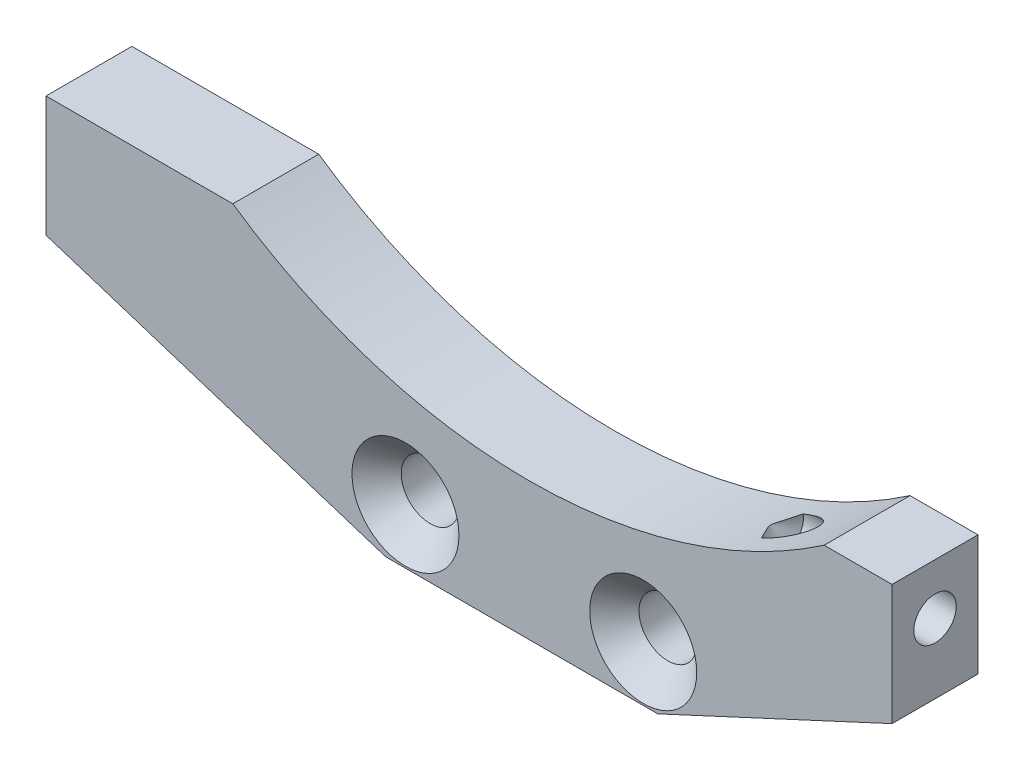
SolidWorks part; units mm, degrees
ref_plane "Piano frontale" through (0, 0, 0) normal (0, 0, 1) x (1, 0, 0)
ref_plane "Piano superiore" through (0, 0, 0) normal (0, 1, 0) x (1, 0, 0)
ref_plane "Piano destro" through (0, 0, 0) normal (1, 0, 0) x (0, 0, -1)
sketch "Schizzo4" plane through (0, 0, 0) normal (0, 0, 1) x (1, 0, 0)
  line L0 (0, 0) -> (16.02, 0)
  line L1 (16.02, 0) -> (29.82, 6.4)
  line L2 (29.82, 6.4) -> (29.82, 13.5)
  line L3 (29.82, 13.5) -> (-20, 13.5)
  line L4 (-20, 13.5) -> (-20, 6.4)
  line L5 (-20, 6.4) -> (0, 0)
  arc A0 (-9, 13.5) -> (25.82, 13.5) centre (8.41, 38.8656) ccw
  point P10 (8.41, 8.1)
  dimension "D8" = 5.4
  dimension "D1" = 49.82
  dimension "D2" = 7.1
  dimension "D3" = 13.8
  dimension "D4" = 13.5
  dimension "D5" = 20
  dimension "D6" = 11
  dimension "D7" = 4
extrude "Estrusione-Estrusione1" add sketch "Schizzo4" along normal blind 5.06 contours A0 L3 L4 L5 L0 L1 L2
ref_plane "Piano1" through (4.91, 0, 0) normal (-1, 0, 0) x (0, 0, 1)
hole_wizard "Foro filettato M3x0.5-1" positions "Schizzo9" profile "Schizzo7" tap size "M3x0.5" standard "Ansi Metric"
sketch "Schizzo9" plane through (-20, 0, 0) normal (-1, 0, 0) x (0, 0, 1)
  line L0 (5.06, 13.5) -> (0, 13.5) construction
  line L3 (2.53, 10.5) -> (2.53, 6.4) construction
  line L4 (5.06, 6.4) -> (0, 6.4) construction
  point P0 (2.53, 10.5)
  point P16 (2.53, 6.4)
  dimension "D1" = 3
sketch "Schizzo7" plane through (-20, 10.5, 2.53) normal (0, 1, 0) x (0, 0, 1)
  line L0 (0, 0) -> (0, 9.7511)
  line L1 (0, 9.7511) -> (1.25, 9)
  line L2 (1.25, 9) -> (1.25, 0)
  line L5 (1.25, 0) -> (0, 0)
  line L10 (0, 9.7511) -> (-1.25, 9) construction
  line L11 (0, -6.35) -> (0, 107.95) construction
  dimension "Tap Drill Dia." = 2.5
  dimension "Tap Drill Depth" = 9
  dimension "Drill Angle" = 118
cosmetic thread "Filettatura del foro1" parameters "D1"=9, "D2"=3
mirror "Specchia1" about plane through (4.91, 0, 0) normal (-1, 0, 0) of "Foro filettato M3x0.5-1"
hole_wizard "Foro svasato per Vite M3-2" positions "Schizzo10" profile "Schizzo11" countersink size "M3" standard "Ansi Metric" end condition through all
sketch "Schizzo10" plane through (-33.4387, -29.3291, 5.06) normal (0, 0, 1) x (1, 0, 0)
  point P0 (34.6055, 32.5791)
  point P2 (48.6055, 32.5791)
sketch "Schizzo11" plane through (1.1669, 3.25, 5.06) normal (1, 0, 0) x (0, -1, 0)
  line L0 (0, 0) -> (0, 5.06)
  line L1 (0, 5.06) -> (1.7, 5.06)
  line L2 (1.7, 5.06) -> (1.7, 1.45)
  line L3 (1.7, 1.45) -> (3.15, 0)
  line L4 (3.15, 0) -> (0, 0)
  line L5 (-1.7, 1.45) -> (-3.15, 0) construction
  line L6 (0, -6.35) -> (0, 107.95) construction
  dimension "Thru Hole Dia." = 3.4
  dimension "Thru Hole Depth" = 5.06
  dimension "Near C'Sink Dia." = 6.3
  dimension "Near C'Sink Angle" = 90
